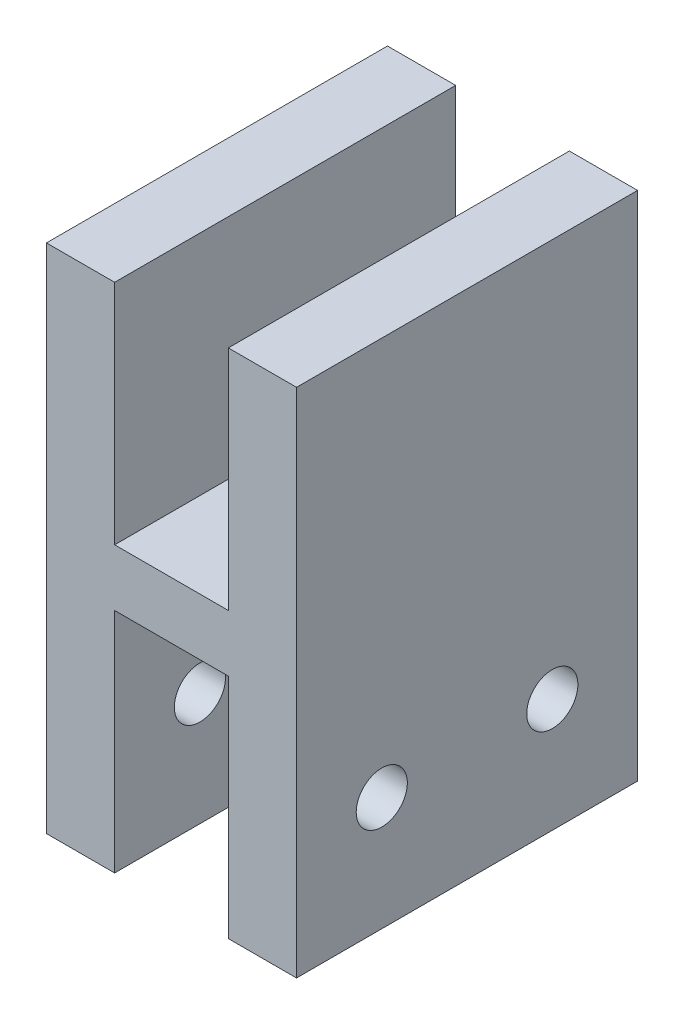
SolidWorks part; units mm, degrees
material "ABS"
ref_plane "Piano frontale" through (0, 0, 0) normal (0, 0, 1) x (1, 0, 0)
ref_plane "Piano superiore" through (0, 0, 0) normal (0, 1, 0) x (1, 0, 0)
ref_plane "Piano destro" through (0, 0, 0) normal (1, 0, 0) x (0, 0, -1)
sketch "Schizzo1" plane through (0, 0, 0) normal (0, 0, 1) x (1, 0, 0)
  line L0 (11, -25) -> (11, 20)
  line L1 (11, -25) -> (5, -25)
  line L2 (5, -25) -> (5, -5)
  line L3 (5, -5) -> (-5, -5)
  line L4 (-5, -5) -> (-5, -25)
  line L5 (-5, -25) -> (-11, -25)
  line L6 (-11, -25) -> (-11, 20)
  line L7 (11, 20) -> (5, 20)
  line L8 (5, 20) -> (5, 0)
  line L9 (5, 0) -> (-5, 0)
  line L10 (-5, 0) -> (-5, 20)
  line L11 (-5, 20) -> (-11, 20)
  point P1 (0, 0)
  point P15 (11.9741, -17.284)
  point P16 (5, -5.4874)
  dimension "D1" = 10
  dimension "D2" = 5
  dimension "D3" = 6
  dimension "D4" = 45
  dimension "D5" = 20
extrude "Estrusione-Estrusione1" add sketch "Schizzo1" along normal blind 30
hole_wizard "Foro per Vite M4-1" positions "Schizzo3D1" profile "Schizzo3" hole size "M4" standard "ISO"
sketch3d "Schizzo3D1"
  line L0 (-11, -25, 15) -> (-11, -15, 15) construction
  line L1 (-11, -25, 30) -> (-11, -25, 0) construction
  line L2 (-11, -15, 15) -> (-11, -15, 7.5) construction
  line L4 (-11, -15, 15) -> (-11, -15, 22.5) construction
  point P17 (-11, -15, 7.5)
  point P19 (-11, -15, 22.5)
  point P22 (0, 0, 0)
  point P23 (0, 0, 0)
  dimension "D1" = 10
  dimension "D2" = 15
sketch "Schizzo3" plane through (-11, -15, 22.5) normal (0, 1, 0) x (0, 0, 1)
  line L0 (0, 0) -> (0, 31.3519)
  line L1 (0, 31.3519) -> (2.25, 30)
  line L2 (2.25, 30) -> (2.25, 0)
  line L5 (2.25, 0) -> (0, 0)
  line L10 (0, 31.3519) -> (-2.25, 30) construction
  line L11 (0, -6.35) -> (0, 107.95) construction
  dimension "Hole Dia." = 4.5
  dimension "Hole Depth" = 30
  dimension "Drill Angle" = 118
